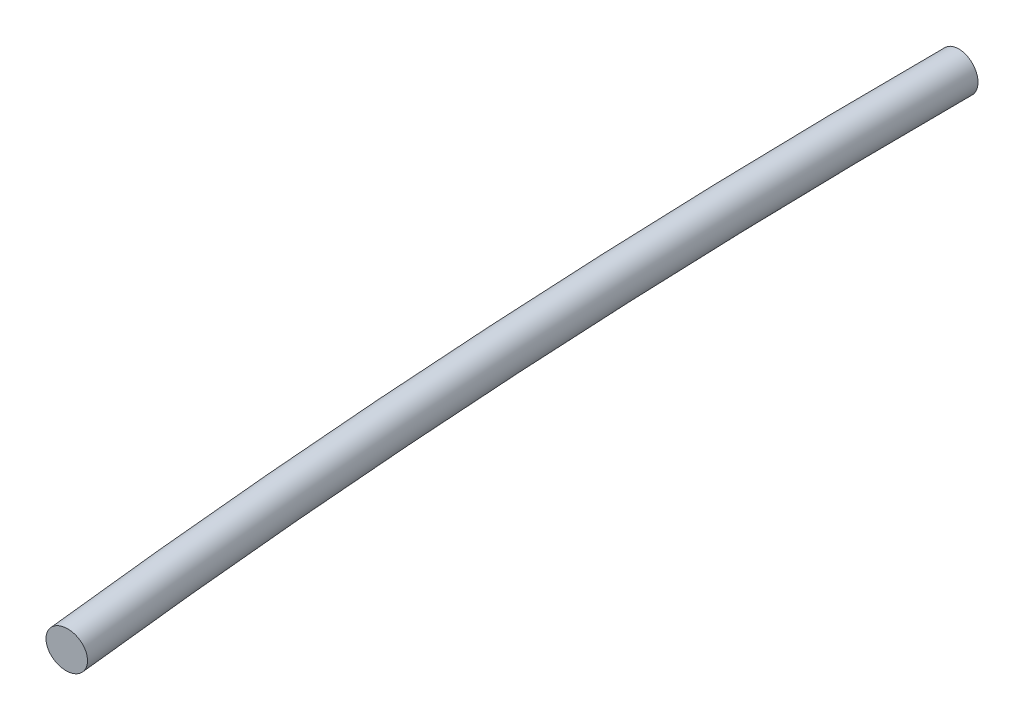
SolidWorks part; units mm, degrees
ref_plane "Front" through (0, 0, 0) normal (0, 0, 1) x (1, 0, 0)
ref_plane "Top" through (0, 0, 0) normal (0, 1, 0) x (1, 0, 0)
ref_plane "Right" through (0, 0, 0) normal (1, 0, 0) x (0, 0, -1)
sketch "Sketch1" plane through (0, 0, 0) normal (0, 0, 1) x (1, 0, 0)
  circle A0 centre (875.0463, -11491.6751) radius 50.8
ref_plane "Plane1" through (-4687.6951, -8379.8865, 0) normal (0.4882, 0.8727, 0) x (0.8456, -0.473, 0.2476)
sketch "Sketch2" plane through (-4687.6951, -8379.8865, 0) normal (0.4882, 0.8727, 0) x (0.8456, -0.473, 0.2476)
  line L0 (6175.5587, 1577.9086) -> (6475.6526, 403.4125) construction
  line L1 (6881.3773, -755.2968) -> (7058.4082, -1259.99) construction
  line L2 (6175.5587, 1577.9086) -> (6881.3773, -755.2968) construction
  line L3 (6503.031, 403.6109) -> (6528.468, 411.3059) construction
  arc A0 (6175.5587, 1577.9086) -> (6881.3773, -755.2968) centre (33267.3968, 8500.1074) ccw
  ellipse E2 centre (9782.5307, 2499.5211) end of major axis (8194.4323, 8714.96) minor radius 3722.8506 (5843.7912, 3949.7101) -> (6175.5587, 1577.9086) ccw construction
  point P6 (6810.7023, -551.2929)
  point P8 (6558.8113, 221.4608)
  point P10 (6329.4857, 1001.2089)
  point P11 (6503.031, 403.6109)
  dimension "D1" = 2438.4
  dimension "D2" = 215.9
  dimension "D3" = 812.8
  dimension "D4" = 812.8
  dimension "D5" = 1219.2
  dimension "D6" = 26.5754
sweep "Sweep1" add profiles "Sketch1" path "Sketch2"
